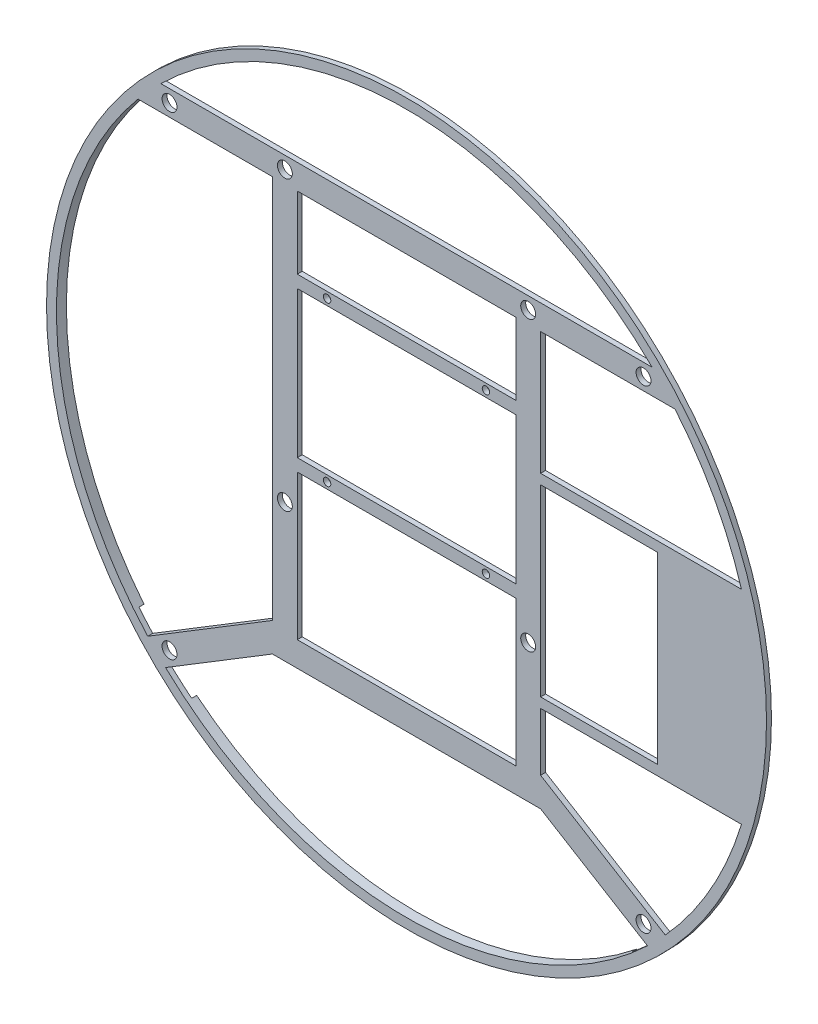
SolidWorks part; units mm, degrees
material "ABS"
ref_plane "Ebene vorne" through (0, 0, 0) normal (0, 0, 1) x (1, 0, 0)
ref_plane "Ebene oben" through (0, 0, 0) normal (0, 1, 0) x (1, 0, 0)
ref_plane "Ebene rechts" through (0, 0, 0) normal (1, 0, 0) x (0, 0, -1)
sketch "Skizze1" plane through (0, 0, 0) normal (0, 0, 1) x (1, 0, 0)
  circle A0 centre (0, 0) radius 72.5
  circle A1 centre (0, 0) radius 70.5
  dimension "D1" = 145
  dimension "D2" = 2
extrude "Base Ring" add sketch "Skizze1" along normal blind 1
sketch "Placement Sketch" plane through (0, 0, 0) normal (0, 0, 1) x (1, 0, 0)
  line L0 (0, 143.896) -> (0, -183.6418) construction
  line L9 (-28, 49.4797) -> (28, 49.4797) construction
  line L10 (-28, 49.4797) -> (-28, -35.5203) construction
  line L11 (-28, -35.5203) -> (28, -35.5203) construction
  line L12 (28, 49.4797) -> (28, -35.5203) construction
  line L13 (-28, 49.4797) -> (28, -35.5203) construction
  line L14 (-28, -35.5203) -> (28, 49.4797) construction
  line L15 (47.7297, 47.7297) -> (-47.7297, 47.7297) construction
  line L16 (-47.7297, 47.7297) -> (-47.7297, -47.7297) construction
  line L17 (-47.7297, -47.7297) -> (47.7297, -47.7297) construction
  line L18 (47.7297, -47.7297) -> (47.7297, 47.7297) construction
  line L19 (-24.5, 47.7297) -> (24.5, 47.7297) construction
  line L20 (-24.5, 47.7297) -> (-24.5, -10.2703) construction
  line L21 (-24.5, -10.2703) -> (24.5, -10.2703) construction
  line L22 (24.5, 47.7297) -> (24.5, -10.2703) construction
  line L23 (-24.5, 47.7297) -> (24.5, -10.2703) construction
  line L24 (-24.5, -10.2703) -> (24.5, 47.7297) construction
  circle A0 centre (0, 0) radius 67.5 construction
  circle A1 centre (0, 0) radius 47.7297 construction
  point P2 (0, 6.9797)
  point P8 (0, 18.7297)
  dimension "D1" = 135
  dimension "D2" = 56
  dimension "D3" = 85
  dimension "D5" = 49
  dimension "D6" = 58
  dimension "D7" = 1.75
sketch "Skizze2" plane through (0, 0, 0) normal (0, 0, 1) x (1, 0, 0)
  line L0 (-28, 49.4797) -> (28, 49.4797) construction
  line L1 (-54.0789, 50.2297) -> (0, 50.2297)
  line L2 (-54.0789, 50.2297) -> (-54.0789, 45.2297)
  line L3 (-54.0789, 45.2297) -> (0, 45.2297)
  line L4 (0, 50.2297) -> (0, 45.2297)
  line L5 (-54.0789, 50.2297) -> (0, 45.2297) construction
  line L6 (-54.0789, 45.2297) -> (0, 50.2297) construction
  line L7 (-47.7297, -47.7297) -> (-28, -35.5203) construction
  line L8 (0, 143.896) -> (0, -183.6418) construction
  line L9 (47.7297, 47.7297) -> (-47.7297, 47.7297) construction
  line L10 (-24.5, 47.7297) -> (-24.5, -10.2703) construction
  line L11 (-27, -33.0203) -> (-22, -33.0203)
  line L12 (-27, -33.0203) -> (-27, 45.2297)
  line L13 (-27, 45.2297) -> (-22, 45.2297)
  line L14 (-22, -33.0203) -> (-22, 45.2297)
  line L15 (-27, -33.0203) -> (-22, 45.2297) construction
  line L16 (-27, 45.2297) -> (-22, -33.0203) construction
  line L17 (-28, -35.5203) -> (28, -35.5203) construction
  line L18 (-27, -38.0203) -> (0, -38.0203)
  line L19 (-27, -38.0203) -> (-27, -33.0203)
  line L20 (-27, -33.0203) -> (0, -33.0203)
  line L21 (0, -38.0203) -> (0, -33.0203)
  line L22 (-27, -38.0203) -> (0, -33.0203) construction
  line L23 (-27, -33.0203) -> (0, -38.0203) construction
  line L24 (-52.1174, -47.4766) -> (-27, -32.1644)
  line L25 (-48.5251, -51.1426) -> (-27, -38.0203)
  line L26 (0, 28.2297) -> (-22, 28.2297)
  line L27 (0, 28.2297) -> (0, 30.7297)
  line L28 (0, 30.7297) -> (-22, 30.7297)
  line L29 (-22, 28.2297) -> (-22, 30.7297)
  line L30 (0, 28.2297) -> (-22, 30.7297) construction
  line L31 (0, 30.7297) -> (-22, 28.2297) construction
  line L33 (0, -3.7703) -> (-22, -3.7703)
  line L34 (0, -3.7703) -> (0, -1.2703)
  line L35 (0, -1.2703) -> (-22, -1.2703)
  line L36 (-22, -3.7703) -> (-22, -1.2703)
  line L37 (0, -3.7703) -> (-22, -1.2703) construction
  line L38 (0, -1.2703) -> (-22, -3.7703) construction
  circle A0 centre (0, 0) radius 70.5
  circle A1 centre (0, 0) radius 70.5 construction
  point P5 (-27.0394, 47.7297)
  point P19 (-24.5, 6.1047)
  point P25 (-13.5, -35.5203)
  point P35 (-11, 29.4797)
  point P42 (-11, -2.5203)
  dimension "D1" = 5
  dimension "D2" = 5
  dimension "D3" = 5
  dimension "D4" = 5
  dimension "D5" = 2.5
  dimension "D6" = 2.5
  dimension "D7" = 20
  dimension "D8" = 2.5
  dimension "D9" = 32
extrude "Raspberry Frame" add sketch "Skizze2" along normal up to surface (1 mm away) contours L1 A0 L3 L4 | L11 L14 L3 L12 | L24 A0 L25 L19 L12 | L18 L21 L20 L11 L19 | L27 L26 L29 L28 | L34 L33 L36 L35 up to face at (72.5, 0, 1)
hole_wizard "Screws I" positions "Skizze3" profile "Skizze4" hole size "Ø3.5" standard "ISO" end condition through all
sketch "Skizze3" plane through (0, 0, 1) normal (0, 0, 1) x (1, 0, 0)
  point P0 (-47.7297, -47.7297)
  point P2 (-24.5, -10.2703)
  point P4 (-47.7297, 47.7297)
  point P6 (-24.5, 47.7297)
sketch "Skizze4" plane through (-47.7297, -47.7297, 1) normal (1, 0, 0) x (0, -1, 0)
  line L0 (0, 0) -> (0, 1)
  line L1 (0, 1) -> (1.5, 1)
  line L2 (1.5, 1) -> (1.5, 0)
  line L5 (1.5, 0) -> (0, 0)
  line L11 (0, -6.35) -> (0, 107.95) construction
  dimension "Bohrerdurchmesser" = 3
  dimension "Bohrungstiefe" = 1
hole_wizard "Fan Screws" positions "Skizze5" profile "Skizze6" hole size "Ø1.5" standard "ISO" end condition through all
sketch "Skizze5" plane through (0, 0, 1) normal (0, 0, 1) x (1, 0, 0)
  line L1 (-16, 29.4797) -> (0, 29.4797) construction
  line L2 (0, 143.896) -> (0, -183.6418) construction
  line L3 (0, 30.7297) -> (-22, 30.7297) construction
  line L4 (0, 28.2297) -> (-22, 28.2297) construction
  point P0 (-16, 29.4797)
  point P2 (-16, -2.5203)
  dimension "D1" = 32
  dimension "D2" = 16
sketch "Skizze6" plane through (-16, 29.4797, 1) normal (1, 0, 0) x (0, -1, 0)
  line L0 (0, 0) -> (0, 1)
  line L1 (0, 1) -> (0.75, 1)
  line L2 (0.75, 1) -> (0.75, 0)
  line L5 (0.75, 0) -> (0, 0)
  line L11 (0, -6.35) -> (0, 107.95) construction
  dimension "Bohrerdurchmesser" = 1.5
  dimension "Bohrungstiefe" = 1
mirror "Mirror I" about plane through (0, 0, 0) normal (1, 0, 0) of "Fan Screws", "Screws I", "Raspberry Frame"
sketch "Skizze7" plane through (0, 0, 1) normal (0, 0, 1) x (1, 0, 0)
  line L0 (0, 0) -> (72.5, 0) construction
  line L1 (52.1174, -47.4766) -> (27, -32.1644) construction
  line L2 (27, -32.1644) -> (27, 45.2297) construction
  line L3 (50.5, -20.5) -> (70.5, -20.5)
  line L4 (50.5, -20.5) -> (50.5, 20.5)
  line L5 (50.5, 20.5) -> (70.5, 20.5)
  line L6 (70.5, -20.5) -> (70.5, 20.5)
  line L7 (50.5, -20.5) -> (70.5, 20.5) construction
  line L8 (50.5, 20.5) -> (70.5, -20.5) construction
  line L13 (50.5, 20.5) -> (27, 20.5)
  line L14 (50.5, 20.5) -> (50.5, 18.5)
  line L15 (50.5, 18.5) -> (27, 18.5)
  line L16 (27, 20.5) -> (27, 18.5)
  line L18 (50.5, -20.5) -> (27, -20.5)
  line L19 (50.5, -20.5) -> (50.5, -18.5)
  line L20 (50.5, -18.5) -> (27, -18.5)
  line L21 (27, -20.5) -> (27, -18.5)
  circle A0 centre (0, 0) radius 72.5 construction
  arc A1 (54.0789, 45.2297) -> (52.1174, -47.4766) centre (0, 0) cw
  point P4 (60.5, 0)
  arc M11 (54.0789, 45.2297) -> (52.1174, -47.4766) centre (0, 0) cw
  dimension "D1" = 41
  dimension "D2" = 20
  dimension "D3" = 2
  dimension "D4" = 2
extrude "Top Cover" add sketch "Skizze7" against normal up to surface (1 mm away) contours L5 L4 L3 M11 | L13 L16 L15 L14 | L19 L18 L21 L20 up to face at (16.75, 29.4797, 0)
sketch "Skizze8" plane through (0, 0, 0) normal (0, 0, -1) x (-1, 0, 0)
  line L0 (-27, 20.5) -> (-67.4537, 20.5) construction
  line L3 (0, 0) -> (-109.4958, 0) construction
  line L4 (-50.5, 20.5) -> (-68.1249, 20.5)
  line L5 (-50.5, 20.5) -> (-50.5, 20)
  line L6 (-50.5, 20) -> (-68.1249, 20)
  line L7 (-68.1249, 20.5) -> (-68.1249, 20)
  line L8 (-27, -20.5) -> (-67.4537, -20.5) construction
  line L9 (-50.5, -20.5) -> (-68.1249, -20.5)
  line L10 (-50.5, -20.5) -> (-50.5, -20)
  line L11 (-50.5, -20) -> (-68.1249, -20)
  line L12 (-68.1249, -20.5) -> (-68.1249, -20)
  line L14 (-50.5, -18.5) -> (-50.5, 18.5) construction
  arc A0 (-67.4537, 20.5) -> (-67.4537, -20.5) centre (0, 0) cw
  arc A1 (-68.1249, 20) -> (-68.1249, -20) centre (0, 0) cw
  arc A2 (-54.0789, 45.2297) -> (-67.4537, 20.5) centre (0, 0) ccw construction
  arc A3 (-67.4537, -20.5) -> (-52.1174, -47.4766) centre (0, 0) ccw construction
  point P8 (0, 0)
  point P10 (-67.4537, 20.5)
  point P25 (0, 0)
  point P26 (-67.4195, -20.5)
  point P27 (0, 0)
  point P28 (-50.6168, -20.5)
  dimension "D1" = 0.5
  dimension "D2" = 0.5
extrude "Inner Ring" add sketch "Skizze8" along normal blind 1
sketch "Skizze9" plane through (0, 0, 0) normal (0, 0, -1) x (-1, 0, 0)
  line L0 (-47.7297, -47.7297) -> (0, 0) construction
  line L2 (-45.9619, -56.5685) -> (-38.8909, -49.4975)
  line L3 (-45.9619, -56.5685) -> (-56.5685, -45.9619)
  line L4 (-56.5685, -45.9619) -> (-49.4975, -38.8909)
  line L5 (-38.8909, -49.4975) -> (-49.4975, -38.8909)
  line L6 (-45.9619, -56.5685) -> (-49.4975, -38.8909) construction
  line L7 (-56.5685, -45.9619) -> (-38.8909, -49.4975) construction
  circle A0 centre (0, 0) radius 72.5 construction
  dimension "D1" = 15
extrude "Lower Cover Cut" cut sketch "Skizze9" along normal through all
pattern_circular "Cover Cut Rotation" count 4 over 360 about axis through (0, 0, 0) along (0, 0, 1) of "Lower Cover Cut"
equation "\"D_outer\"=145"
equation "\"D1@Skizze1\"=\"D_outer\""
